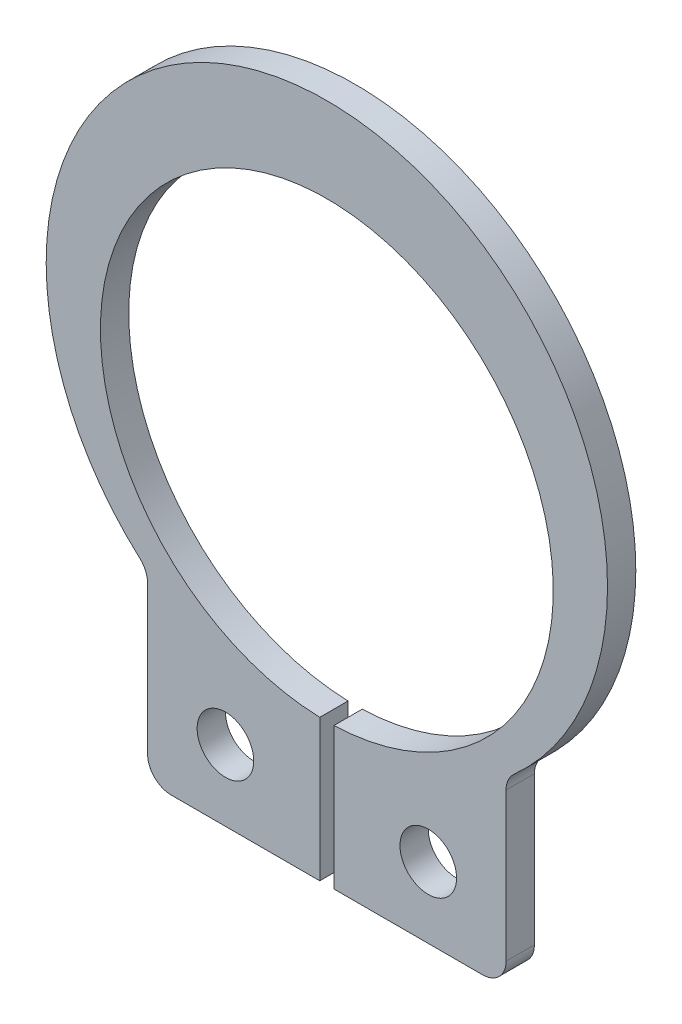
SolidWorks part; units mm, degrees
ref_plane "Front Plane" through (0, 0, 0) normal (0, 0, 1) x (1, 0, 0)
ref_plane "Top Plane" through (0, 0, 0) normal (0, 1, 0) x (1, 0, 0)
ref_plane "Right Plane" through (0, 0, 0) normal (1, 0, 0) x (0, 0, -1)
sketch "Sketch1" plane through (0, 0, 0) normal (0, 0, 1) x (1, 0, 0)
  line L0 (-3.8, -4.1575) -> (-3.8, -7.3)
  line L1 (-3.3, -7.8) -> (-0.15, -7.8)
  line L5 (-0.15, -7.8) -> (-0.15, -4.7977)
  line L6 (0.15, -4.7977) -> (0.15, -7.8)
  line L10 (0.15, -7.8) -> (3.3, -7.8)
  line L11 (3.8, -7.3) -> (3.8, -4.1575)
  line L12 (0, 0) -> (0, 6.6) construction
  arc A0 (3.9667, -3.7849) -> (-3.9667, -3.7849) centre (0, 0.65) ccw
  arc A1 (-3.9667, -3.7849) -> (-3.8, -4.1575) centre (-4.3, -4.1575) cw
  arc A2 (-3.8, -7.3) -> (-3.3, -7.8) centre (-3.3, -7.3) ccw
  arc A4 (-0.15, -4.7977) -> (0.15, -4.7977) centre (0, 0) cw
  arc A6 (3.3, -7.8) -> (3.8, -7.3) centre (3.3, -7.3) ccw
  arc A7 (3.8, -4.1575) -> (3.9667, -3.7849) centre (4.3, -4.1575) cw
  dimension "D1" = 0.3
  dimension "REC_D2_s" = 9.6
  dimension "D2" = 0.5
  dimension "D4" = 0.65
  dimension "REC_MSM_1" = 11.9
  dimension "D3" = 0.5
  dimension "REC_MSM_2" = 7.6
  dimension "REC_A_s" = 3
  dimension "REC_B_s" = 1.8
extrude "Boss-Extrude1" add sketch "Sketch1" against normal blind 0.6
sketch "Sketch2" plane through (0, 0, 0) normal (0, 0, 1) x (1, 0, 0)
  line L0 (-3.8, -6.3) -> (3.8, -6.3) construction
  line L1 (-3.8, -4.1575) -> (-3.8, -7.3) construction
  line L2 (3.8, -7.3) -> (3.8, -4.1575) construction
  line L3 (-3.3, -7.8) -> (-0.15, -7.8) construction
  line L4 (0, 0) -> (0, -7.8) construction
  circle A0 centre (-2.15, -6.3) radius 0.6
  circle A1 centre (2.15, -6.3) radius 0.6
  dimension "REC_D0_s" = 1.2
  dimension "REC_MSM_4" = 1.5
  dimension "REC_MSM_3" = 4.3
extrude "Cut-Extrude1" cut sketch "Sketch2" against normal through all
other "DeleteFace1" [suppressed]
sketch "Sketch3" [suppressed] plane through (0, 0, 0) normal (0, 0, 1) x (1, 0, 0)
  line L0 (-3.8, -6.3) -> (3.8, -6.3) construction
  line L4 (0, 0) -> (0, -7.8) construction
  line L5 (0.15, -7.8) -> (3.3, -7.8) construction
  line L6 (-3.3, -7.8) -> (-0.15, -7.8) construction
  line L7 (-2.15, -5.7) -> (2.15, -5.7)
  line L8 (2.15, -6.9) -> (-2.15, -6.9)
  line L9 (-3.8, -4.1575) -> (-3.8, -7.3) construction
  line L10 (3.8, -7.3) -> (3.8, -4.1575) construction
  arc A0 (-2.15, -5.7) -> (-2.15, -6.9) centre (-2.15, -6.3) ccw
  arc A1 (2.15, -6.9) -> (2.15, -5.7) centre (2.15, -6.3) ccw
  dimension "REC_D0_s" = 1.2
  dimension "REC_MSM_4" = 1.5
  dimension "REC_MSM_3" = 4.3
extrude "Cut-Extrude2" [suppressed] cut sketch "Sketch3" against normal through all
